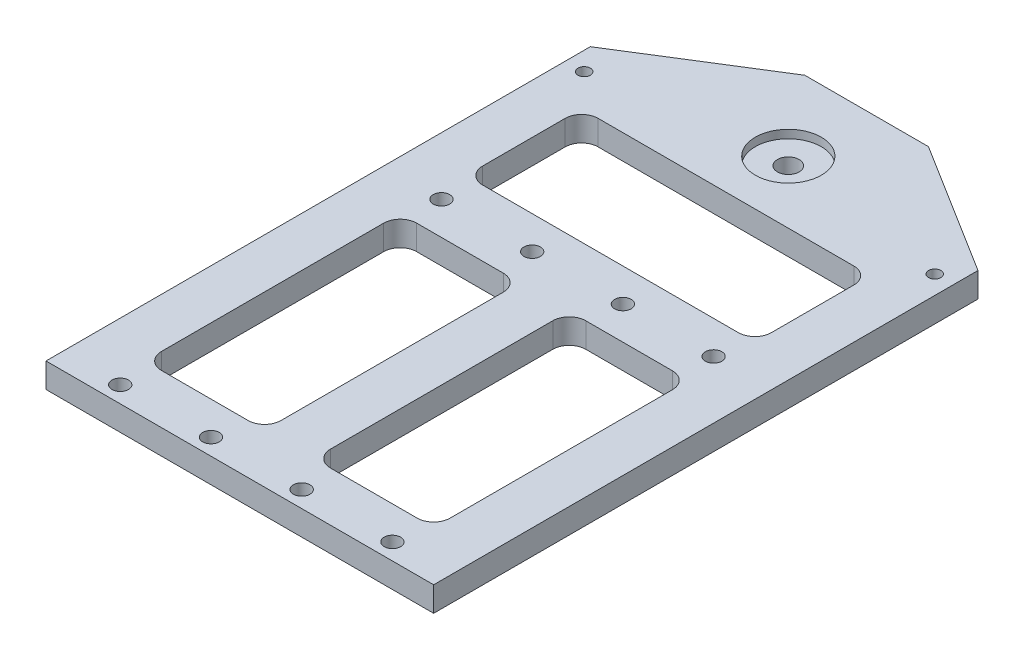
SolidWorks part; units mm, degrees
material "6061-T6 (SS)"
ref_plane "Front" through (0, 0, 0) normal (0, 0, 1) x (1, 0, 0)
ref_plane "Top" through (0, 0, 0) normal (0, 1, 0) x (1, 0, 0)
ref_plane "Right" through (0, 0, 0) normal (1, 0, 0) x (0, 0, -1)
sketch "Sketch1" plane through (0, 0, 0) normal (0, 1, 0) x (1, 0, 0)
  line L1 (0, 0) -> (298.45, 0)
  line L2 (0, 0) -> (0, 482.6)
  line L3 (0, 482.6) -> (298.45, 482.6)
  line L4 (298.45, 0) -> (298.45, 482.6)
  dimension "D1" = 298.45
  dimension "D2" = 482.6
extrude "Boss-Extrude1" add sketch "Sketch1" along normal blind 19.05
hole_wizard "1/2 (0.5) Diameter Hole1" positions "Sketch2" profile "Sketch3" hole size "1/2" standard "ANSI Inch" end condition through all
sketch "Sketch2" plane through (0, 19.05, 0) normal (0, 1, 0) x (1, 0, 0)
  line L0 (0, 0) -> (298.45, 0) construction
  line L1 (0, 482.6) -> (0, 0) construction
  point P0 (44.45, 12.7)
  dimension "D1" = 12.7
  dimension "D2" = 44.45
sketch "Sketch3" plane through (44.45, 19.05, -12.7) normal (1, 0, 0) x (0, 0, 1)
  line L0 (0, 0) -> (0, 19.05)
  line L1 (0, 19.05) -> (6.35, 19.05)
  line L2 (6.35, 19.05) -> (6.35, 0)
  line L5 (6.35, 0) -> (0, 0)
  line L11 (0, -6.35) -> (0, 107.95) construction
  dimension "Thru Hole Dia." = 12.7
  dimension "Thru Hole Depth" = 19.05
pattern_linear "LPattern1" count 4 spacing 69.85 along (1, 0, 0) count 2 spacing 247.2944 along (0, 0, -1) of "1/2 (0.5) Diameter Hole1"
hole_wizard "3/8 (0.375) Diameter Hole1" positions "Sketch4" profile "Sketch5" hole size "3/8" standard "ANSI Inch" end condition through all
sketch "Sketch4" plane through (0, 19.05, 0) normal (0, 1, 0) x (1, 0, 0)
  line L0 (0, 0) -> (298.45, 0) construction
  line L1 (298.45, 0) -> (298.45, 482.6) construction
  point P0 (284.1625, 400.05)
  point P2 (14.2875, 400.05)
  dimension "D1" = 400.05
  dimension "D2" = 400.05
  dimension "D3" = 14.2875
  dimension "D4" = 269.875
sketch "Sketch5" plane through (284.1625, 19.05, -400.05) normal (1, 0, 0) x (0, 0, 1)
  line L0 (0, 0) -> (0, 19.05)
  line L1 (0, 19.05) -> (4.7625, 19.05)
  line L2 (4.7625, 19.05) -> (4.7625, 0)
  line L5 (4.7625, 0) -> (0, 0)
  line L11 (0, -6.35) -> (0, 107.95) construction
  dimension "Thru Hole Dia." = 9.525
  dimension "Thru Hole Depth" = 19.05
sketch "Sketch6" plane through (0, 19.05, 0) normal (0, 1, 0) x (1, 0, 0)
  line L0 (0, 482.6) -> (0, 0) construction
  circle A0 centre (149.225, 422.275) radius 25.4
  circle A1 centre (44.45, 259.9944) radius 6.35 construction
  dimension "D1" = 50.8
  dimension "D3" = 162.2806
  dimension "D2" = 149.225
extrude "Cut-Extrude1" cut sketch "Sketch6" against normal blind 6.35
hole_wizard "3/4-10 Tapped Hole1" positions "Sketch7" profile "Sketch8" tap size "3/4-10" standard "ANSI Inch" end condition through all
sketch "Sketch7" plane through (0, 0, 0) normal (0, -1, 0) x (-1, 0, 0)
  line L0 (-298.45, 0) -> (-298.45, 482.6) construction
  circle A0 centre (-254, 259.9944) radius 6.35 construction
  point P0 (-149.225, 422.275)
  dimension "D1" = 149.225
  dimension "D2" = 162.2806
cosmetic thread "Hole Thread1" parameters "D2"=19.05
sketch "Sketch8" plane through (149.225, 0, -422.275) normal (1, 0, 0) x (0, 0, -1)
  line L0 (0, 0) -> (0, 19.05)
  line L1 (0, 19.05) -> (8.3337, 19.05)
  line L2 (8.3337, 19.05) -> (8.3337, 0)
  line L5 (8.3337, 0) -> (0, 0)
  line L11 (0, -6.35) -> (0, 107.95) construction
  dimension "Thru Tap Drill Dia." = 16.6675
  dimension "Thru Tap Drill Depth" = 19.05
sketch "Sketch9" plane through (0, 0, 0) normal (0, -1, 0) x (1, 0, 0)
  circle A0 centre (149.225, -422.275) radius 12.7
  dimension "D1" = 25.4
split line "Split Line1" [suppressed]
sketch "Sketch10" plane through (0, 19.05, 0) normal (0, 1, 0) x (1, 0, 0)
  line L0 (0, 482.6) -> (0, 0) construction
  line L1 (38.1, 38.1) -> (130.175, 38.1)
  line L2 (38.1, 38.1) -> (38.1, 234.5944)
  line L3 (38.1, 234.5944) -> (130.175, 234.5944)
  line L4 (130.175, 38.1) -> (130.175, 234.5944)
  line L5 (168.275, 38.1) -> (260.35, 38.1)
  line L6 (168.275, 38.1) -> (168.275, 234.5944)
  line L7 (168.275, 234.5944) -> (260.35, 234.5944)
  line L8 (260.35, 38.1) -> (260.35, 234.5944)
  line L9 (38.1, 285.3944) -> (130.175, 285.3944)
  line L10 (38.1, 285.3944) -> (38.1, 361.95)
  line L11 (38.1, 361.95) -> (130.175, 361.95)
  line L12 (130.175, 285.3944) -> (130.175, 361.95)
  line L13 (168.275, 285.3944) -> (260.35, 285.3944)
  line L14 (168.275, 285.3944) -> (168.275, 361.95)
  line L15 (168.275, 361.95) -> (260.35, 361.95)
  line L16 (260.35, 285.3944) -> (260.35, 361.95)
  line L17 (298.45, 0) -> (298.45, 482.6) construction
  line L18 (0, 0) -> (298.45, 0) construction
  circle A0 centre (44.45, 259.9944) radius 6.35 construction
  circle A1 centre (254, 259.9944) radius 6.35 construction
  circle A2 centre (14.2875, 400.05) radius 4.7625 construction
  circle A3 centre (284.1625, 400.05) radius 4.7625 construction
  dimension "D5" = 25.4
  dimension "D6" = 25.4
  dimension "D10" = 38.1
  dimension "D1" = 38.1
  dimension "D2" = 38.1
  dimension "D3" = 38.1
  dimension "D4" = 38.1
  dimension "D7" = 25.4
  dimension "D8" = 25.4
  dimension "D9" = 38.1
  dimension "D11" = 38.1
  dimension "D12" = 38.1
  dimension "D13" = 38.1
  dimension "D14" = 38.1
extrude "Cut-Extrude2" cut sketch "Sketch10" against normal through all
fillet "Fillet1" radius 12.7 16 edges at (260.35, 9.525, -285.3944) (130.175, 9.525, -285.3944) (130.175, 9.525, -38.1) (260.35, 9.525, -38.1) (168.275, 9.525, -285.3944) (38.1, 9.525, -285.3944) (38.1, 9.525, -38.1) (168.275, 9.525, -38.1) (130.175, 9.525, -234.5944) (260.35, 9.525, -234.5944) (130.175, 9.525, -361.95) (260.35, 9.525, -361.95) (168.275, 9.525, -234.5944) (168.275, 9.525, -361.95) (38.1, 9.525, -234.5944) (38.1, 9.525, -361.95)
sketch "Sketch11" plane through (0, 19.05, 0) normal (0, 1, 0) x (1, 0, 0)
  line L0 (0, 482.6) -> (0, 419.1)
  line L1 (0, 482.6) -> (0, 0) construction
  line L2 (0, 419.1) -> (101.6, 482.6)
  line L3 (298.45, 482.6) -> (0, 482.6) construction
  line L4 (101.6, 482.6) -> (0, 482.6)
  line L5 (298.45, 482.6) -> (196.85, 482.6)
  line L6 (196.85, 482.6) -> (298.45, 419.1)
  line L7 (298.45, 0) -> (298.45, 482.6) construction
  line L8 (298.45, 419.1) -> (298.45, 482.6)
  dimension "D1" = 101.6
  dimension "D2" = 63.5
  dimension "D3" = 63.5
  dimension "D4" = 101.6
extrude "Cut-Extrude3" cut sketch "Sketch11" against normal through all
sketch "Sketch12" plane through (0, 19.05, 0) normal (0, 1, 0) x (1, 0, 0)
  line L0 (50.8, 285.3944) -> (117.475, 285.3944) construction
  line L1 (50.8, 285.3944) -> (247.65, 285.3944)
  line L2 (38.1, 298.0944) -> (38.1, 361.5944)
  line L3 (50.8, 374.2944) -> (247.65, 374.2944)
  line L4 (260.35, 298.0944) -> (260.35, 361.5944)
  line L5 (38.1, 349.25) -> (38.1, 298.0944) construction
  line L6 (260.35, 298.0944) -> (260.35, 349.25) construction
  arc A0 (260.35, 298.0944) -> (247.65, 285.3944) centre (247.65, 298.0944) cw
  arc A1 (260.35, 361.5944) -> (247.65, 374.2944) centre (247.65, 361.5944) ccw
  arc A2 (38.1, 361.5944) -> (50.8, 374.2944) centre (50.8, 361.5944) cw
  arc A3 (50.8, 285.3944) -> (38.1, 298.0944) centre (50.8, 298.0944) cw
  point P12 (260.35, 285.3944)
  point P15 (260.35, 374.2944)
  dimension "D5" = 12.7
  dimension "D1" = 0
  dimension "D2" = 0
  dimension "D3" = 0
  dimension "D4" = 88.9
extrude "Cut-Extrude4" cut sketch "Sketch12" against normal through all
